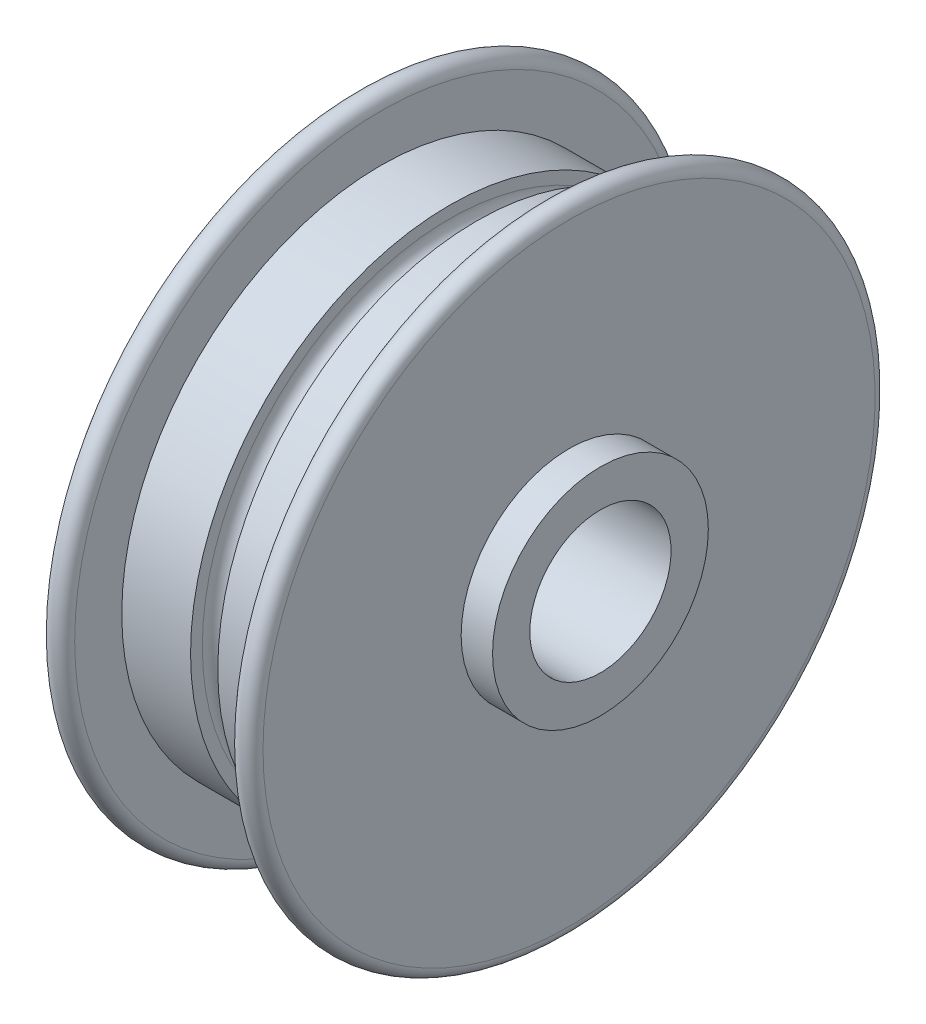
SolidWorks part; units mm, degrees
ref_plane "Ön Düzlem" through (0, 0, 0) normal (0, 0, 1) x (1, 0, 0)
ref_plane "Üst Düzlem" through (0, 0, 0) normal (0, 1, 0) x (1, 0, 0)
ref_plane "Sağ Düzlem" through (0, 0, 0) normal (1, 0, 0) x (0, 0, -1)
sketch "Çizim1" plane through (0, 0, 0) normal (0, 0, 1) x (1, 0, 0)
  line L0 (0.0006, 9) -> (0.0006, 13.75)
  line L1 (0.0006, 13.75) -> (4.0006, 13.75)
  line L2 (4.0006, 13.75) -> (4.0006, 39)
  line L4 (7.0006, 39) -> (7.0006, 33)
  line L5 (7.0006, 33) -> (15.7659, 33)
  line L6 (15.7659, 33) -> (15.7659, 31.5)
  line L8 (19.2353, 31.5) -> (19.2353, 33)
  line L9 (19.2353, 33) -> (28.0006, 33)
  line L10 (28.0006, 33) -> (28.0006, 39)
  line L12 (31.0006, 39) -> (31.0006, 13.75)
  line L13 (31.0006, 13.75) -> (35.0006, 13.75)
  line L14 (35.0006, 13.75) -> (35.0006, 9)
  line L16 (0.0006, 9) -> (35.0006, 9)
  line L17 (0, 0) -> (65.9737, 0) construction
  arc A0 (15.7659, 31.5) -> (19.2353, 31.5) centre (17.5006, 31.2692) ccw
  arc A1 (7.0006, 39) -> (4.0006, 39) centre (5.5006, 39) ccw
  arc A2 (31.0006, 39) -> (28.0006, 39) centre (29.5006, 39) ccw
  dimension "D8" = 3.5
  dimension "D1" = 9
  dimension "D2" = 35
  dimension "D3" = 27
  dimension "D4" = 21
  dimension "D5" = 13.75
  dimension "D6" = 31.5
  dimension "D7" = 33
revolve "Döndür1" add sketch "Çizim1" angle 360 about L17
